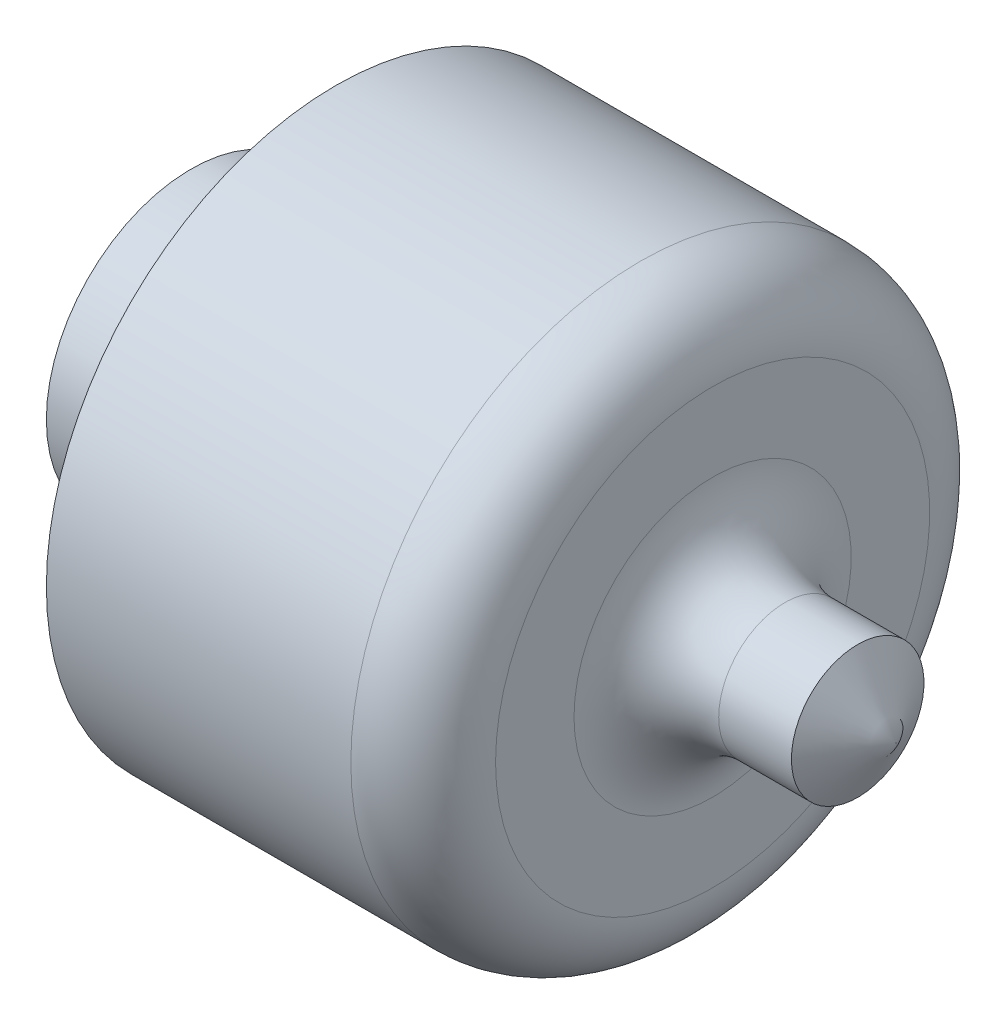
SolidWorks part; units mm, degrees
ref_plane "Plan de face" through (0, 0, 0) normal (0, 0, 1) x (1, 0, 0)
ref_plane "Plan de dessus" through (0, 0, 0) normal (0, 1, 0) x (1, 0, 0)
ref_plane "Plan de droite" through (0, 0, 0) normal (1, 0, 0) x (0, 0, -1)
sketch "Esquisse1" plane through (0, 0, 0) normal (0, 0, 1) x (1, 0, 0)
  line L0 (0, 0) -> (48.7068, 0)
  line L1 (41.039, 4.5793) -> (46.0629, 4.5793)
  line L2 (48.7068, 0) -> (46.0629, 4.5793)
  line L3 (36.039, 9.5793) -> (36.039, 15)
  line L4 (31.039, 20) -> (10, 20)
  line L5 (10, 20) -> (10, 10)
  line L6 (10, 10) -> (0, 10)
  line L7 (0, 10) -> (0, 0)
  line L8 (0, 0) -> (67.6841, 0) construction
  arc A0 (41.039, 4.5793) -> (36.039, 9.5793) centre (41.039, 9.5793) cw
  arc A1 (31.039, 20) -> (36.039, 15) centre (31.039, 15) cw
  dimension "D1" = 5
  dimension "D2" = 5
  dimension "D3" = 20
  dimension "D4" = 60
  dimension "D5" = 10
  dimension "D6" = 10
revolve "Révolution1" add sketch "Esquisse1" angle 360 about L8
